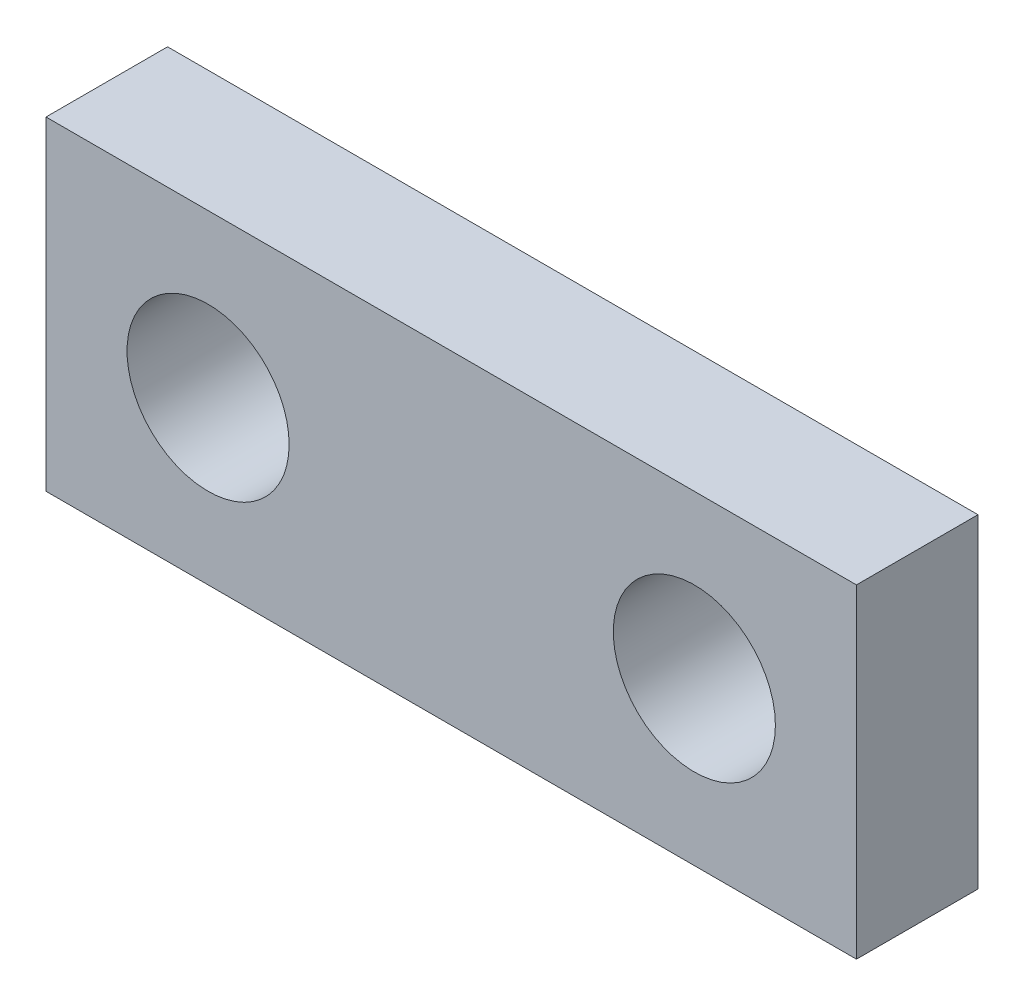
SolidWorks part; units mm, degrees
ref_plane "Alzado" through (0, 0, 0) normal (0, 0, 1) x (1, 0, 0)
ref_plane "Planta" through (0, 0, 0) normal (0, 1, 0) x (1, 0, 0)
ref_plane "Vista lateral" through (0, 0, 0) normal (1, 0, 0) x (0, 0, -1)
sketch "Croquis1" plane through (0, 0, 0) normal (0, 0, 1) x (1, 0, 0)
  line L0 (10, 4) -> (-10, 4)
  line L1 (10, 4) -> (10, -4)
  line L2 (10, -4) -> (-10, -4)
  line L3 (-10, -4) -> (-10, 4)
  circle A0 centre (6, 0) radius 2
  circle A1 centre (-6, 0) radius 2
  point P4 (0, 4)
  point P7 (0, 0)
  point P11 (10, 0)
  point P13 (0, 0)
  dimension "D1" = 4
  dimension "D2" = 4
  dimension "D3" = 6
  dimension "D4" = 6
  dimension "D5" = 20
  dimension "D6" = 8
extrude "Saliente-Extruir1" add sketch "Croquis1" along normal blind 3
